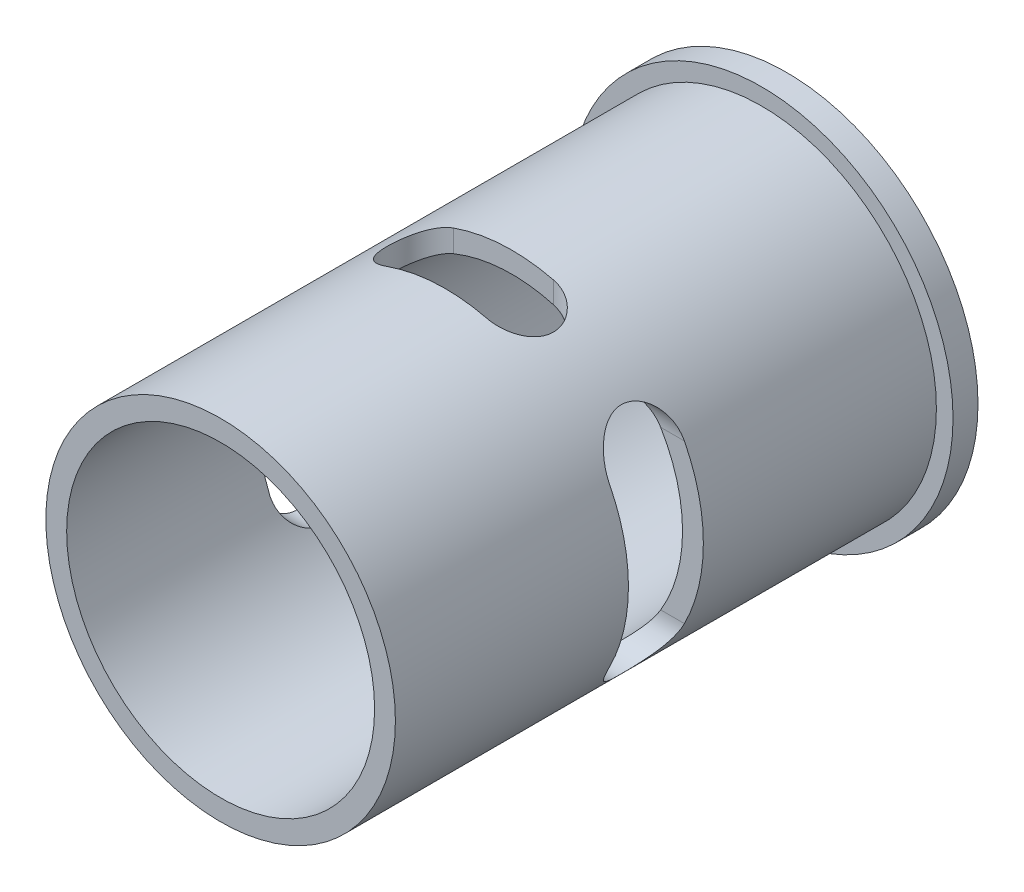
SolidWorks part; units mm, degrees
ref_plane "Plan1" through (0, 0, 0) normal (0, 0, 1) x (1, 0, 0)
ref_plane "Plan2" through (0, 0, 0) normal (0, 1, 0) x (1, 0, 0)
ref_plane "Plan3" through (0, 0, 0) normal (1, 0, 0) x (0, 0, -1)
ref_plane "Plan4" through (10.5, 0, 0) normal (1, 0, 0) x (0, 0, -1)
ref_plane "Plan5" through (0, 10.5, 0) normal (0, 1, 0) x (-1, 0, 0)
ref_plane "Plan6" through (-11, 0, 0) normal (1, 0, 0) x (0, 0, -1)
sketch "Esquisse1" plane through (0, 0, 0) normal (0, 0, 1) x (1, 0, 0)
  circle A0 centre (0, 0) radius 10.5
  dimension "D1" = 21
extrude "Base-Extrusion" add sketch "Esquisse1" along normal blind 32.5
sketch "Esquisse2" plane through (0, 0, 32.5) normal (0, 0, 1) x (1, 0, 0)
  circle A0 centre (0, 0) radius 9.25
  dimension "D1" = 18.5
sketch "Esquisse3" plane through (0, 0, 0) normal (0, 0, -1) x (-1, 0, 0)
  circle A0 centre (0, 0) radius 11.5
  dimension "D1" = 23
extrude "Boss.-Extru.1" add sketch "Esquisse3" along normal blind 1.5
extrude "Enlèv. mat.-Extru.1" cut sketch "Esquisse2" against normal through all
sketch "Esquisse4" plane through (10.5, 0, 0) normal (1, 0, 0) x (0, 0, -1)
  line L1 (0, 11.5) -> (0, -11.5) construction
  line L7 (-14, 4.75) -> (-14, -4.75)
  line L8 (-18.5, 4.75) -> (-18.5, -4.75)
  arc A0 (-18.5, -4.75) -> (-14, -4.75) centre (-16.25, -4.75) ccw
  arc A1 (-14, 4.75) -> (-18.5, 4.75) centre (-16.25, 4.75) ccw
  dimension "D3" = 4.5
  dimension "D4" = 4.5
  dimension "D1" = 14
extrude "Enlèv. mat.-Extru.2" cut sketch "Esquisse4" against normal up to next
sketch "Esquisse5" plane through (0, 10.5, 0) normal (0, 1, 0) x (-1, 0, 0)
  line L3 (5.5, -3) -> (5.5, 34) construction
  line L4 (-4.5, 34) -> (-4.5, -3.9678) construction
  line L5 (10.5, 0) -> (10.5, 32.5) construction
  line L8 (3.5, 19) -> (-2.5, 19)
  line L9 (-2.5, 15) -> (3.5, 15)
  arc A0 (3.5, 15) -> (3.5, 19) centre (3.5, 17) ccw
  arc A1 (-2.5, 19) -> (-2.5, 15) centre (-2.5, 17) ccw
  dimension "D3" = 4
  dimension "D4" = 4
  dimension "D5" = 5
  dimension "D6" = 10
extrude "Enlèv. mat.-Extru.3" cut sketch "Esquisse5" against normal through all
sketch "Esquisse7" plane through (-11, 0, 0) normal (1, 0, 0) x (0, 0, -1)
  line L3 (3, -5.5) -> (-35, -5.5) construction
  line L4 (3, 5.5) -> (-35, 5.5) construction
  line L5 (-32.5, -10.5) -> (-19, -10.5) construction
  line L8 (-17, -3.5) -> (-17, 3.5)
  line L9 (-21, -3.5) -> (-21, 3.5)
  arc A0 (-17, 3.5) -> (-21, 3.5) centre (-19, 3.5) ccw
  arc A1 (-21, -3.5) -> (-17, -3.5) centre (-19, -3.5) ccw
  dimension "D5" = 4
  dimension "D6" = 4
  dimension "D3" = 11
  dimension "D4" = 5
extrude "Enlèv. mat.-Extru.5" cut sketch "Esquisse7" against normal up to surface (2.4377 mm away)
